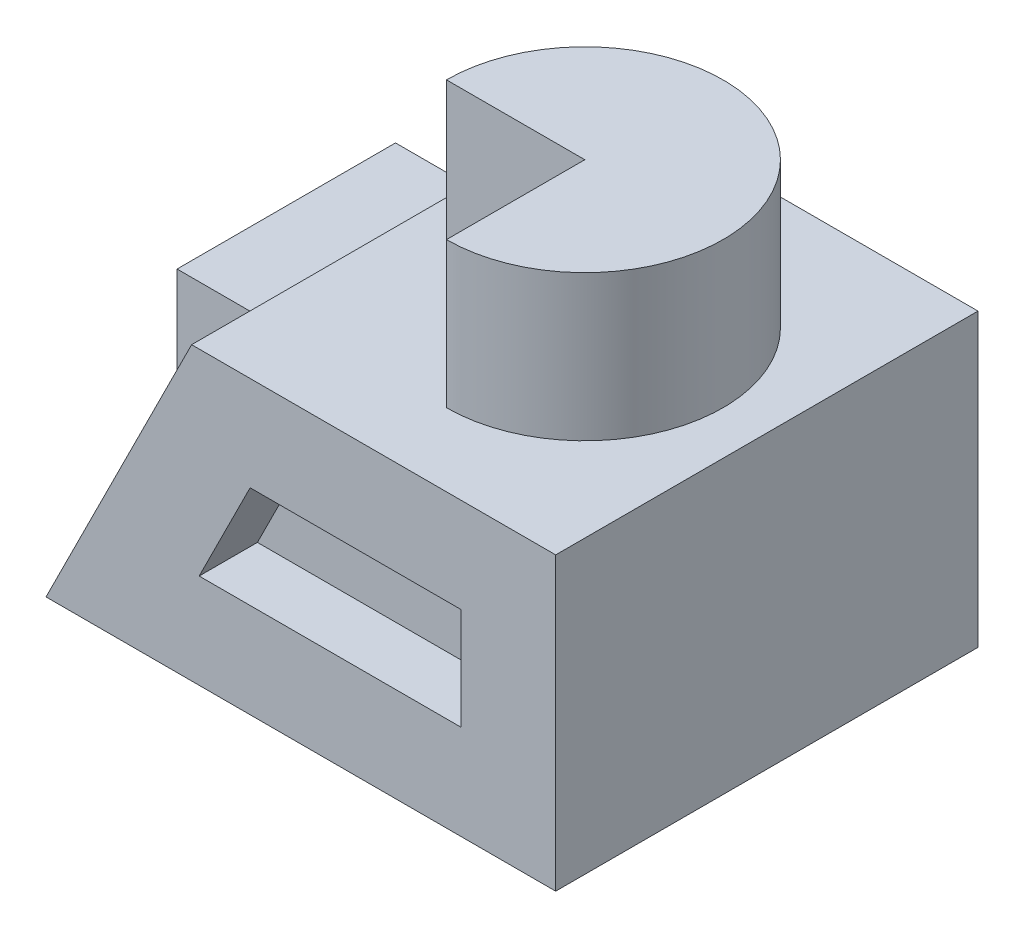
SolidWorks part; units mm, degrees
ref_plane "Спереди" through (0, 0, 0) normal (0, 0, 1) x (1, 0, 0)
ref_plane "Сверху" through (0, 0, 0) normal (0, 1, 0) x (1, 0, 0)
ref_plane "Справа" through (0, 0, 0) normal (1, 0, 0) x (0, 0, -1)
sketch "Эскиз1" plane through (0, 0, 0) normal (0, 0, 1) x (1, 0, 0)
  line L0 (-35, -20) -> (-15, 20)
  line L1 (-35, -20) -> (35, -20)
  line L2 (-35, -20) -> (-35, 20)
  line L3 (-35, 20) -> (35, 20)
  line L4 (35, -20) -> (35, 20)
  line L5 (-35, -20) -> (35, 20) construction
  line L6 (-35, 20) -> (35, -20) construction
  point P0 (0, 0)
  dimension "D1" = 40
  dimension "D2" = 70
  dimension "D3" = 20
extrude "Бобышка-Вытянуть1" add sketch "Эскиз1" along normal blind 58 contours L1 L4 L3 L0
sketch "Эскиз2" plane through (0, 20, 0) normal (0, 1, 0) x (1, 0, 0)
  line L0 (-15, -29) -> (35, -29) construction
  line L1 (-15, -58) -> (-15, 0) construction
  line L2 (35, -58) -> (35, 0) construction
  line L3 (-9, -29) -> (10, -29)
  line L4 (10, -29) -> (10, -48)
  circle A0 centre (10, -29) radius 19
  dimension "D1" = 38
extrude "Бобышка-Вытянуть2" add sketch "Эскиз2" along normal blind 20 contours L0 L4 A0 | L3 L0 A0
sketch "Эскиз3" plane through (0, 0, 58) normal (0, 0, 1) x (1, 0, 0)
  line L14 (22, -7) -> (22, 7)
  line L15 (-13.9656, -7) -> (22, -7)
  line L16 (-6.9656, 7) -> (-13.9656, -7)
  line L17 (22, 7) -> (-6.9656, 7)
  line L18 (22, -7) -> (22, 7)
  line L19 (-13.9656, -7) -> (22, -7)
  line L20 (-6.9656, 7) -> (-13.9656, -7)
  line L21 (22, 7) -> (-6.9656, 7)
  dimension "D1" = 13
extrude "Вырез-Вытянуть1" cut sketch "Эскиз3" against normal blind 8
ref_plane "Плоскость1" through (0, 0, 29) normal (0, 0, 1) x (1, 0, 0)
sketch "Эскиз4" plane through (0, 0, 29) normal (0, 0, 1) x (1, 0, 0)
  line L0 (-31, -12) -> (-31, 14)
  line L1 (-35, -20) -> (-15, 20) construction
  line L2 (-31, 14) -> (-18, 14)
  line L3 (-15, 20) -> (35, 20) construction
  line L4 (-18, 14) -> (-31, -12)
  dimension "D1" = 4
  dimension "D2" = 6
extrude "Бобышка-Вытянуть3" add sketch "Эскиз4" against normal blind 15 and the other way blind 15
